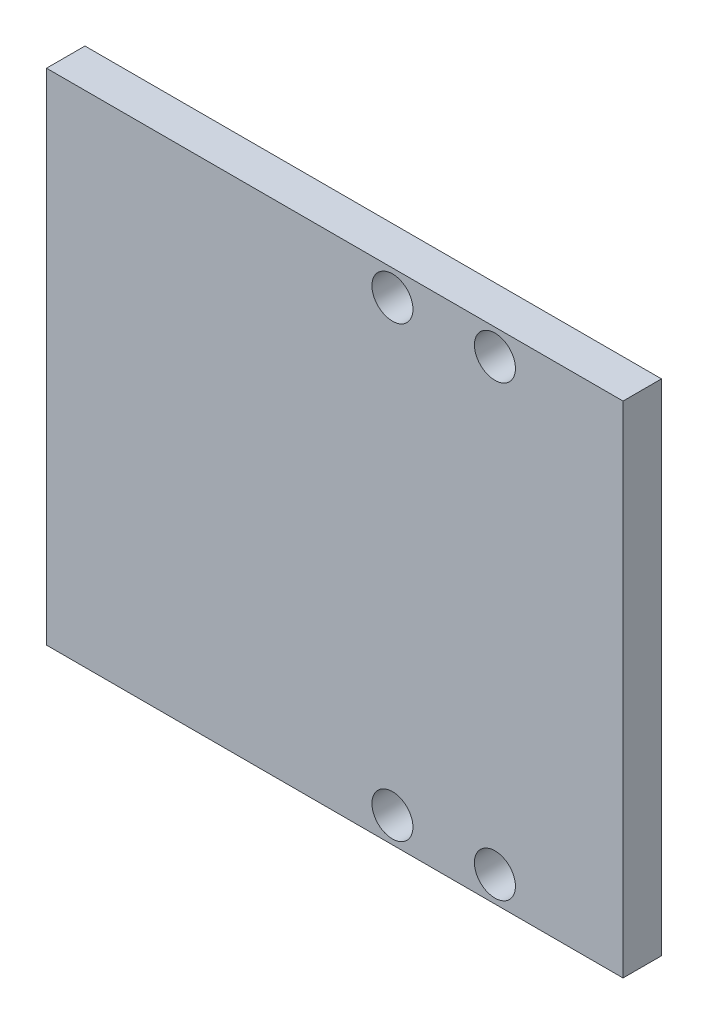
SolidWorks part; units mm, degrees
ref_plane "前视基准面" through (0, 0, 0) normal (0, 0, 1) x (1, 0, 0)
ref_plane "上视基准面" through (0, 0, 0) normal (0, 1, 0) x (1, 0, 0)
ref_plane "右视基准面" through (0, 0, 0) normal (1, 0, 0) x (0, 0, -1)
sketch "Sketch1" plane through (0, 0, 0) normal (0, 0, 1) x (1, 0, 0)
  line L0 (70, -18.2375) -> (50.8838, -18.2375) construction
  line L1 (70, 20.7625) -> (25, 20.7625)
  line L2 (70, 20.7625) -> (70, -18.2375)
  line L3 (70, -18.2375) -> (25, -18.2375)
  line L4 (25, 20.7625) -> (25, -18.2375)
  circle A0 centre (60, 18.7625) radius 1.6
  circle A1 centre (52, 18.7625) radius 1.6
  circle A2 centre (60, -16.2375) radius 1.6
  circle A3 centre (52, -16.2375) radius 1.6
  dimension "D2" = 3.2
  dimension "D1" = 45
extrude "Boss-Extrude1" add sketch "Sketch1" along normal blind 3
